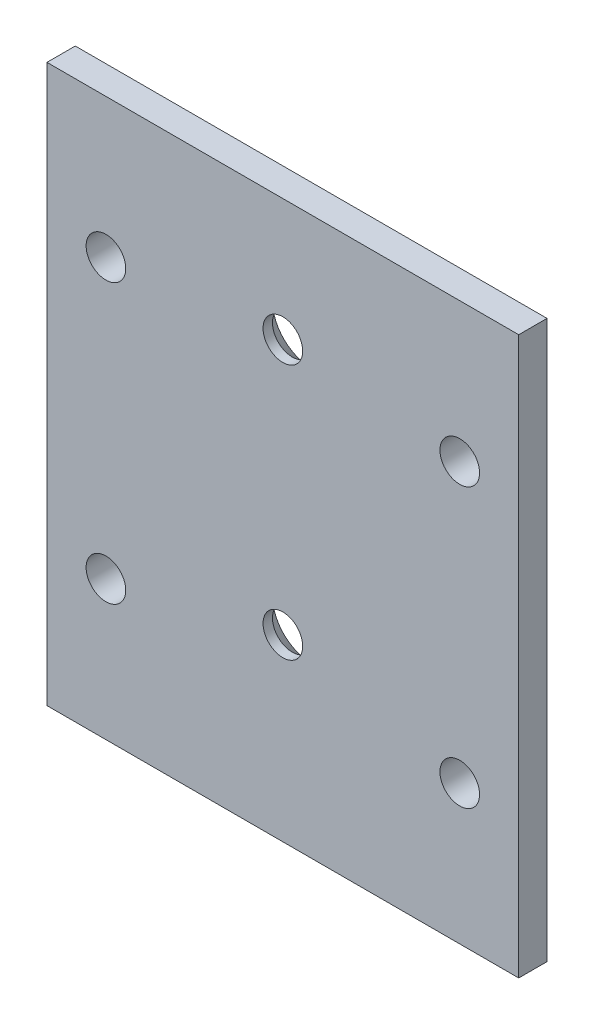
SolidWorks part; units mm, degrees
ref_plane "Piano frontale" through (0, 0, 0) normal (0, 0, 1) x (1, 0, 0)
ref_plane "Piano superiore" through (0, 0, 0) normal (0, 1, 0) x (1, 0, 0)
ref_plane "Piano destro" through (0, 0, 0) normal (1, 0, 0) x (0, 0, -1)
sketch "Schizzo1" plane through (0, 0, 0) normal (0, 0, 1) x (1, 0, 0)
  line L0 (0, 71.8474) -> (25, 71.8474)
  line L2 (25, 71.8474) -> (25, 12.8019)
  line L3 (25, 12.8019) -> (0, 12.8019)
  line L5 (0, 12.8019) -> (0, 71.8474) construction
  line L6 (12.5, 71.8474) -> (25, 42.3246) construction
  line L7 (25, 42.3246) -> (12.5, 12.8019) construction
  line L8 (-25, 12.8019) -> (0, 12.8019)
  line L9 (-25, 71.8474) -> (-25, 12.8019)
  line L10 (0, 71.8474) -> (-25, 71.8474)
  circle A0 centre (18.75, 57.086) radius 2.1
  circle A1 centre (18.75, 27.5632) radius 2.1
  circle A2 centre (-18.75, 27.5632) radius 2.1
  circle A3 centre (-18.75, 57.086) radius 2.1
  circle A4 centre (0, 58.8947) radius 2.1
  circle A5 centre (0, 31.8036) radius 2.1
  dimension "D2" = 4.2
  dimension "D3" = 4.2
  dimension "D1" = 25
extrude "Estrusione-Estrusione1" add sketch "Schizzo1" along normal blind 3
chamfer "Smusso1" distance 2 angle 45 2 edges at (2.1, 31.8036, 0) (2.1, 58.8947, 0)
